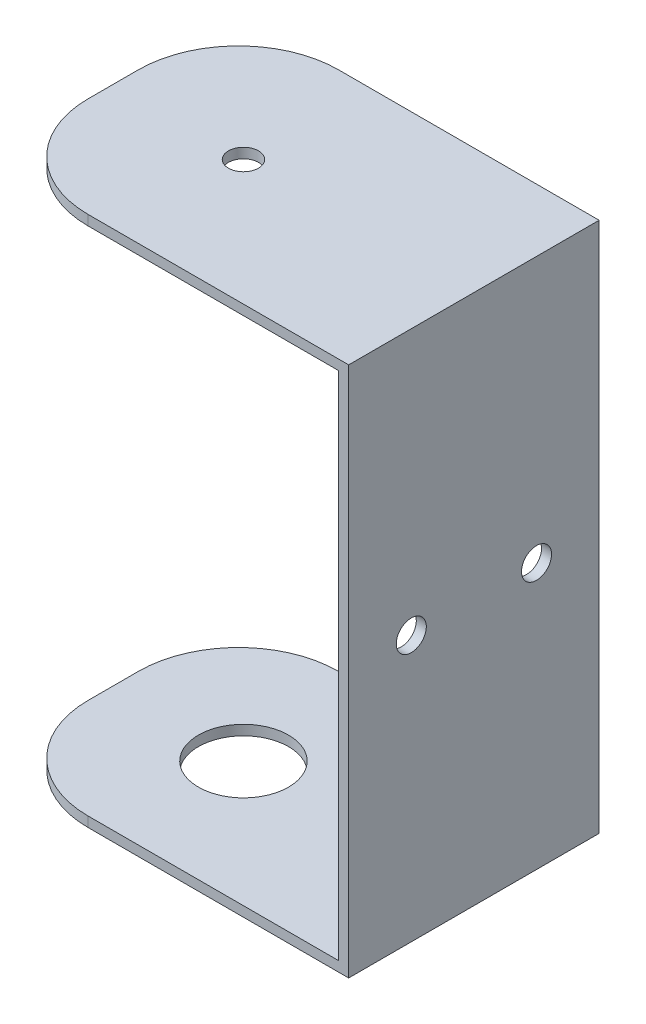
SolidWorks part; units mm, degrees
ref_plane "Alzado" through (0, 0, 0) normal (0, 0, 1) x (1, 0, 0)
ref_plane "Planta" through (0, 0, 0) normal (0, 1, 0) x (1, 0, 0)
ref_plane "Vista lateral" through (0, 0, 0) normal (1, 0, 0) x (0, 0, -1)
sketch "Croquis1" plane through (0, 0, 0) normal (0, 0, 1) x (1, 0, 0)
  line L0 (0, 15.1493) -> (0, -35.8507)
  line L1 (0, -35.8507) -> (-35, -35.8507)
  line L2 (0, 15.1493) -> (-35, 15.1493)
  dimension "D1" = 35
  dimension "D2" = 35
  dimension "D3" = 51
extrude "Extruir-Lámina1" add sketch "Croquis1" along normal blind 25 thin thin type one direction wall 1
sketch "Croquis2" plane through (0, 16.1493, 0) normal (0, 1, 0) x (1, 0, 0)
  circle A0 centre (-22, -12.5) radius 1.5
extrude "Cortar-Extruir1" cut sketch "Croquis2" against normal blind 1
sketch "Croquis5" plane through (0, -36.8507, 0) normal (0, -1, 0) x (1, 0, 0)
  circle A0 centre (-22, 12.5) radius 4.5
extrude "Cortar-Extruir2" cut sketch "Croquis5" against normal blind 1
sketch "Croquis6" plane through (1, 0, 0) normal (1, 0, 0) x (0, 0, -1)
  circle A0 centre (-6.25, -10.3507) radius 1.5
  circle A1 centre (-18.75, -10.3507) radius 1.5
extrude "Cortar-Extruir3" cut sketch "Croquis6" against normal blind 1
fillet "Redondeo1" radius 10 4 edges at (-35, 15.6493, 25) (-35, 15.6493, 0) (-35, -36.3507, 0) (-35, -36.3507, 25)
